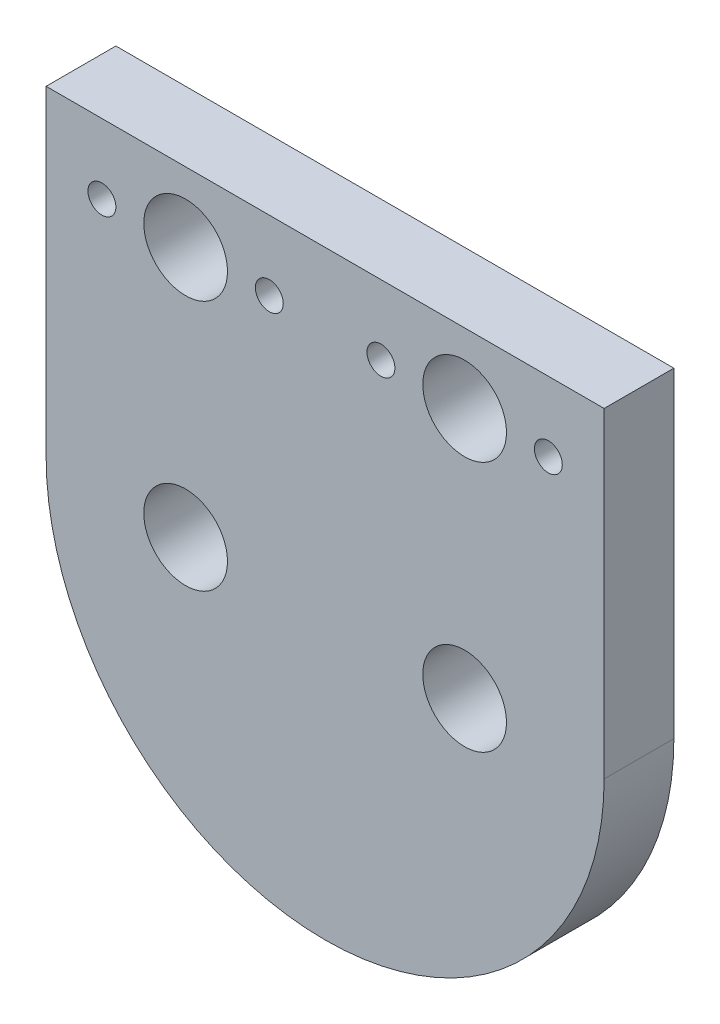
SolidWorks part; units mm, degrees
ref_plane "Alzado" through (0, 0, 0) normal (0, 0, 1) x (1, 0, 0)
ref_plane "Planta" through (0, 0, 0) normal (0, 1, 0) x (1, 0, 0)
ref_plane "Vista lateral" through (0, 0, 0) normal (1, 0, 0) x (0, 0, -1)
sketch "Croquis1" plane through (0, 0, 0) normal (0, 0, 1) x (1, 0, 0)
  line L1 (10, 0) -> (-10, 0) construction
  line L2 (10, 0) -> (10, 18) construction
  line L3 (10, 18) -> (-10, 18) construction
  line L4 (-10, 0) -> (-10, 18) construction
  line L6 (-20, 0) -> (-20, 23)
  line L7 (-20, 23) -> (20, 23)
  line L8 (20, 0) -> (20, 23)
  circle A0 centre (10, 0) radius 3
  circle A1 centre (-10, 0) radius 3
  arc A2 (-20, 0) -> (20, 0) centre (0, 0) ccw
  circle A3 centre (-10, 18) radius 3
  circle A4 centre (10, 18) radius 3
  circle A8 centre (-4, 18) radius 1
  circle A9 centre (-16, 18) radius 1
  circle A10 centre (4, 18) radius 1
  circle A11 centre (16, 18) radius 1
  point P0 (0, 0)
  dimension "D3" = 20
  dimension "D4" = 6
  dimension "D5" = 10
  dimension "D6" = 6
  dimension "D2" = 6
  dimension "D7" = 6
  dimension "D1" = 18
extrude "Saliente-Extruir1" add sketch "Croquis1" along normal blind 5
